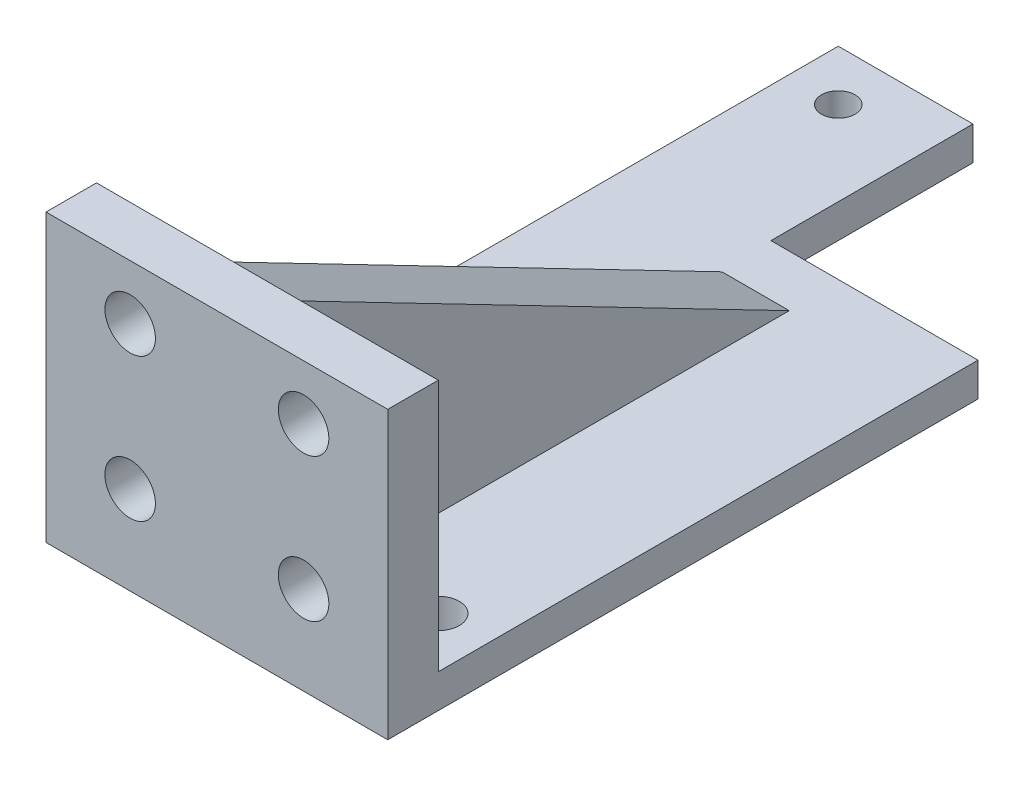
SolidWorks part; units mm, degrees
ref_plane "前视基准面" through (0, 0, 0) normal (0, 0, 1) x (1, 0, 0)
ref_plane "上视基准面" through (0, 0, 0) normal (0, 1, 0) x (1, 0, 0)
ref_plane "右视基准面" through (0, 0, 0) normal (1, 0, 0) x (0, 0, -1)
sketch "草图1" plane through (0, 0, 0) normal (0, 1, 0) x (1, 0, 0)
  line L0 (0, 47.06) -> (0, 44.06)
  line L1 (0, 0) -> (20.3, 0)
  line L2 (0, 0) -> (0, 47.06)
  line L3 (0, 47.06) -> (20.3, 47.06)
  line L4 (20.3, 0) -> (20.3, 47.06)
  line L5 (0, 44.06) -> (3, 44.06)
  line L6 (0, 47.06) -> (8, 47.06)
  line L7 (8, 47.06) -> (8, 35.06)
  line L8 (8, 35.06) -> (20.3, 35.06)
  circle A0 centre (3, 44.06) radius 1
  dimension "D5" = 2
  dimension "D1" = 47.06
  dimension "D2" = 20.3
  dimension "D3" = 3
  dimension "D4" = 3
  dimension "D6" = 8
  dimension "D7" = 12
extrude "凸台-拉伸1" add sketch "草图1" along normal blind 2
sketch "草图2" plane through (0, 2, 0) normal (0, 1, 0) x (1, 0, 0)
  line L0 (0, 0) -> (0, 3)
  line L1 (0, 0) -> (0, 47.06) construction
  line L2 (0, 3) -> (20.3, 3)
  line L3 (20.3, 0) -> (20.3, 35.06) construction
  line L4 (20.3, 3) -> (20.3, 0)
  line L5 (20.3, 0) -> (0, 0)
  dimension "D1" = 3
extrude "凸台-拉伸2" add sketch "草图2" along normal blind 15 contours L5 L0 L2 L4
sketch "草图3" plane through (0, 0, -3) normal (0, 0, -1) x (-1, 0, 0)
  line L0 (-20.3, 17) -> (-20.3, 13.75) construction
  line L1 (-20.3, 17) -> (-20.3, 2) construction
  line L2 (-20.3, 13.75) -> (-15.3, 13.75) construction
  line L3 (-20.3, 9.5) -> (0, 9.5) construction
  line L4 (0, 17) -> (0, 2) construction
  line L5 (0, 17) -> (0, 13.75) construction
  line L6 (0, 13.75) -> (-5, 13.75) construction
  circle A0 centre (-15.3, 13.75) radius 1.5
  circle A1 centre (-15.3, 5.25) radius 1.5
  circle A2 centre (-5, 13.75) radius 1.5
  circle A3 centre (-5, 5.25) radius 1.5
  dimension "D3" = 3
  dimension "D6" = 3
  dimension "D1" = 3.25
  dimension "D2" = 5
  dimension "D4" = 3.25
  dimension "D5" = 5
extrude "切除-拉伸1" cut sketch "草图3" against normal blind 15
sketch "草图6" plane through (0, 0, 0) normal (0, -1, 0) x (1, 0, 0)
  line L0 (20.3, 0) -> (20.3, -6) construction
  line L1 (20.3, 0) -> (20.3, -35.06) construction
  line L2 (20.3, -6) -> (17.3, -6) construction
  circle A0 centre (17.3, -6) radius 1.25
  dimension "D3" = 2.5
  dimension "D1" = 6
  dimension "D2" = 3
extrude "切除-拉伸3" cut sketch "草图6" against normal blind 10
ref_plane "基准面1" through (10.15, 0, 0) normal (-1, 0, 0) x (0, 0, 1)
sketch "草图7" plane through (10.15, 0, 0) normal (-1, 0, 0) x (0, 0, 1)
  line L0 (-3, 17) -> (-3, 2)
  line L1 (-3, 2) -> (-32.0005, 2)
  line L2 (-3, 2) -> (-47.06, 2) construction
  line L3 (-32.0005, 2) -> (-3, 17)
extrude "凸台-拉伸3" add sketch "草图7" along normal mid plane 4
